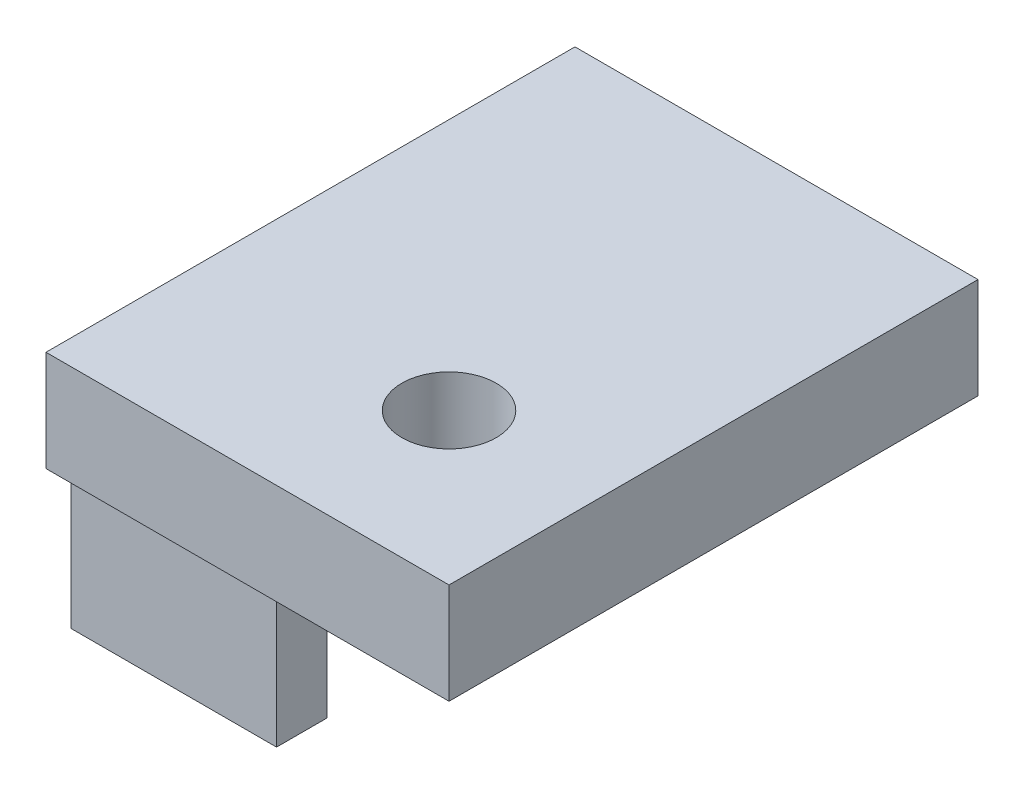
SolidWorks part; units mm, degrees
ref_plane "Front Plane" through (0, 0, 0) normal (0, 0, 1) x (1, 0, 0)
ref_plane "Top Plane" through (0, 0, 0) normal (0, 1, 0) x (1, 0, 0)
ref_plane "Right Plane" through (0, 0, 0) normal (1, 0, 0) x (0, 0, -1)
sketch "Sketch1" plane through (0, 0, 0) normal (0, 1, 0) x (1, 0, 0)
  line L1 (0, 0) -> (9.6, 0)
  line L2 (0, 0) -> (0, -16.8)
  line L3 (0, -16.8) -> (9.6, -16.8)
  line L4 (9.6, 0) -> (9.6, -16.8)
  circle A0 centre (4.8, -12) radius 1.5
  dimension "D3" = 3
  dimension "D1" = 9.6
  dimension "D2" = 16.8
  dimension "D4" = 4.8
  dimension "D5" = 4.8
extrude "Boss-Extrude1" add sketch "Sketch1" along normal blind 3.2
sketch "Sketch3" plane through (0, 0, 0) normal (-1, 0, 0) x (0, 0, 1)
  line L1 (0, 0) -> (16.8, 0)
  line L2 (0, 0) -> (0, 3.2)
  line L3 (0, 3.2) -> (16.8, 3.2)
  line L4 (16.8, 0) -> (16.8, 3.2)
extrude "Boss-Extrude2" add sketch "Sketch3" along normal blind 3.2
sketch "Sketch4" plane through (0, 0, 0) normal (0, -1, 0) x (-1, 0, 0)
  line L0 (3.2, 0) -> (3.2, -16.8) construction
  line L1 (3.2, -14.4) -> (-3.3222, -14.4)
  line L2 (3.2, -14.4) -> (3.2, -16)
  line L3 (3.2, -16) -> (-3.3222, -16)
  line L4 (-3.3222, -14.4) -> (-3.3222, -16)
  line L5 (3.2, -16.8) -> (-9.6, -16.8) construction
  dimension "D1" = 1.6
  dimension "D2" = 2.4
extrude "Boss-Extrude3" add sketch "Sketch4" along normal blind 4.8
sketch "Sketch5" plane through (0, 0, 0) normal (0, -1, 0) x (-1, 0, 0)
  line L0 (3.2, 0) -> (3.2, -14.4) construction
  line L1 (3.2, 0) -> (-3.0896, 0)
  line L2 (3.2, 0) -> (3.2, -1.6)
  line L3 (3.2, -1.6) -> (-3.0896, -1.6)
  line L4 (-3.0896, 0) -> (-3.0896, -1.6)
  dimension "D1" = 1.6
  dimension "D2" = 12.8
extrude "Boss-Extrude4" add sketch "Sketch5" along normal blind 4.8
equation "\"滑动-垂直孔\" = 0.6"
equation "\"滑动-水平孔\" = 0.3"
equation "\"松动-垂直孔\" = 0.3"
equation "\"松动-水平孔\" = 0.1"
equation "\"正常-垂直孔\" = 0.15"
equation "\"正常-水平孔\" = 0"
equation "\"紧缩-垂直孔\" = 0"
equation "\"紧缩-水平孔\" = -0.1"
equation "\"_喷嘴物理宽度\" = 0.8"
equation "\"_喷嘴宽度系数\" = 1"
equation "\"_物理厚度\" = 0.4"
equation "\"_物理厚度系数\" = 2"
equation "\"喷嘴宽度\" = \"_喷嘴物理宽度\" * \"_喷嘴宽度系数\""
equation "\"喷嘴厚度\" = \"_物理厚度\" * \"_物理厚度系数\""
equation "\"D1@Sketch1\"=\"喷嘴宽度\"*12"
equation "\"D2@Sketch1\"=\"喷嘴宽度\"*21"
equation "\"D1@Boss-Extrude1\"=\"喷嘴厚度\"*4"
equation "\"D3@Sketch1\"=\"紧缩-垂直孔\"+3"
equation "\"D4@Sketch1\"=\"喷嘴宽度\"*6"
equation "\"D5@Sketch1\"=\"D4@Sketch1\""
equation "\"D1@Boss-Extrude2\"=\"喷嘴宽度\"*4"
equation "\"D1@Sketch4\"=\"喷嘴宽度\"*2"
equation "\"D2@Sketch4\"=\"喷嘴宽度\"*3"
equation "\"D1@Boss-Extrude3\"=\"喷嘴厚度\"*6"
equation "\"D1@Sketch5\"=\"喷嘴宽度\"*2"
equation "\"D2@Sketch5\"=\"喷嘴宽度\"*16"
equation "\"D1@Boss-Extrude4\"=\"喷嘴厚度\"*6"
